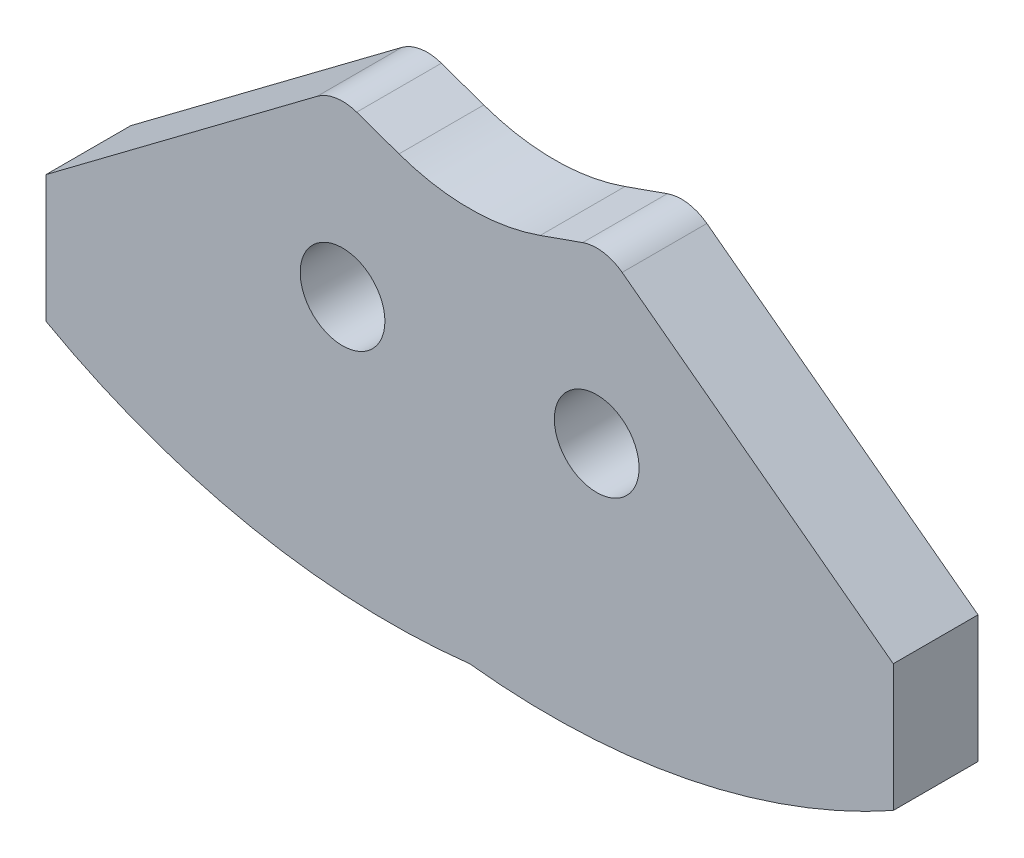
SolidWorks part; units mm, degrees
ref_plane "Płaszczyzna przednia" through (0, 0, 0) normal (0, 0, 1) x (1, 0, 0)
ref_plane "Płaszczyzna górna" through (0, 0, 0) normal (0, 1, 0) x (1, 0, 0)
ref_plane "Płaszczyzna prawa" through (0, 0, 0) normal (1, 0, 0) x (0, 0, -1)
sketch "Szkic1" plane through (0, 0, 0) normal (0, 0, 1) x (1, 0, 0)
  line L6 (0, 10) -> (0, 25)
  line L8 (0, 25) -> (32, 49)
  line L10 (41.6667, 47.9463) -> (36.6667, 49.7141)
  line L11 (100, 10) -> (100, 25)
  line L12 (100, 25) -> (68, 49)
  line L13 (58.3333, 47.9463) -> (63.3333, 49.7141)
  arc A0 (0, 10) -> (50, 0) centre (40.5391, 82.6955) ccw
  circle A2 centre (35, 30) radius 5
  arc A4 (32, 49) -> (36.6667, 49.7141) centre (35, 45) cw
  circle A5 centre (65, 30) radius 5
  arc A6 (100, 10) -> (50, 0) centre (59.4609, 82.6955) cw
  arc A7 (68, 49) -> (63.3333, 49.7141) centre (65, 45) ccw
  arc A8 (58.3333, 47.9463) -> (41.6667, 47.9463) centre (50, 71.5165) cw
  dimension "D1" = 25
extrude "Dodanie-wyciągnięcie1" add sketch "Szkic1" along normal blind 10
